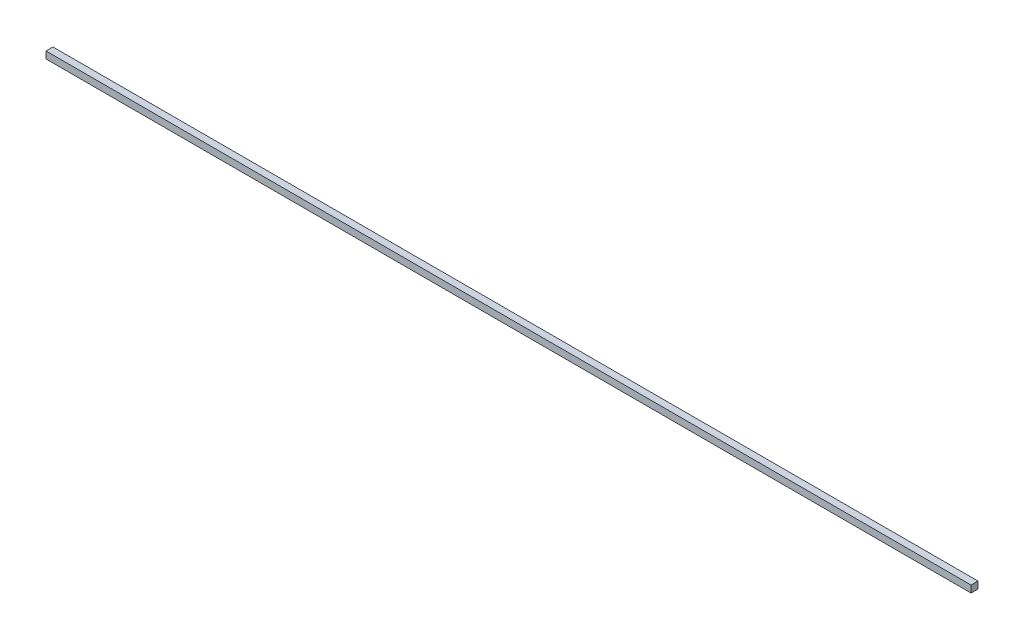
SolidWorks part; units mm, degrees
ref_plane "前视基准面" through (0, 0, 0) normal (0, 0, 1) x (1, 0, 0)
ref_plane "上视基准面" through (0, 0, 0) normal (0, 1, 0) x (1, 0, 0)
ref_plane "右视基准面" through (0, 0, 0) normal (1, 0, 0) x (0, 0, -1)
sketch "Model" plane through (0, 0, 0) normal (0, 0, 1) x (1, 0, 0)
  line L0 (656.2534, 30.8976) -> (1321.9027, 30.8976)
  line L1 (656.2534, 30.8976) -> (656.2534, 35.8976)
  line L2 (656.2534, 35.8976) -> (1321.9027, 35.8976)
  line L3 (1321.9027, 30.8976) -> (1321.9027, 35.8976)
extrude "凸台-拉伸1" add sketch "Model" along normal blind 5
